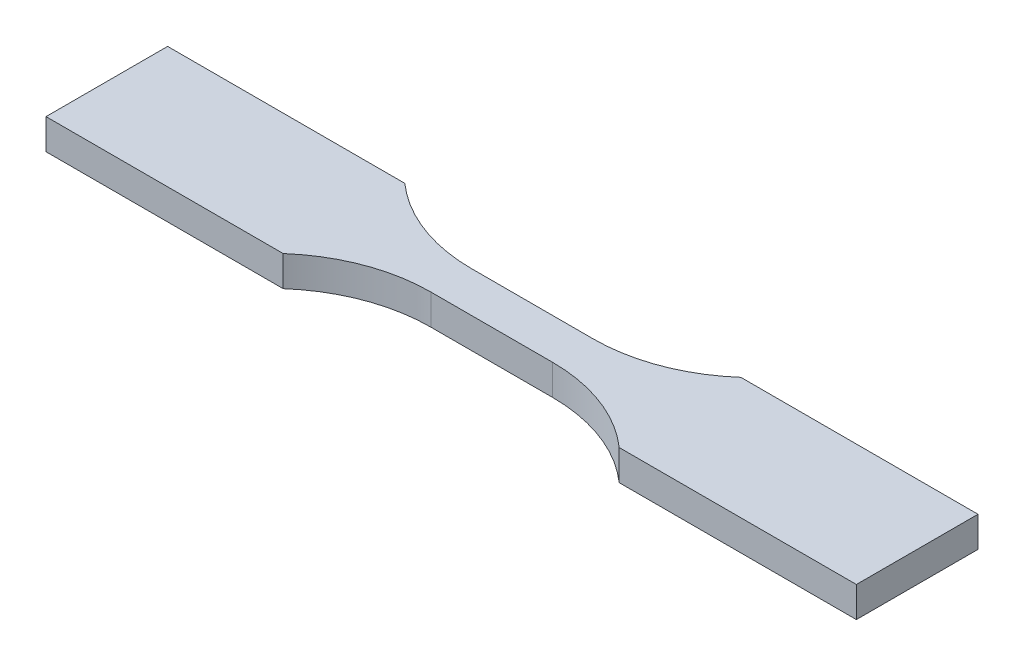
SolidWorks part; units mm, degrees
ref_plane "Front Plane" through (0, 0, 0) normal (0, 0, 1) x (1, 0, 0)
ref_plane "Top Plane" through (0, 0, 0) normal (0, 1, 0) x (1, 0, 0)
ref_plane "Right Plane" through (0, 0, 0) normal (1, 0, 0) x (0, 0, -1)
sketch "Sketch1" plane through (0, 0, 0) normal (0, 1, 0) x (1, 0, 0)
  line L0 (0, 1.59) -> (4.765, 1.59)
  line L2 (0, 0) -> (0, 1.59)
  line L3 (0, 0) -> (31.75, 0)
  line L4 (31.75, 0) -> (31.75, 4.765)
  line L5 (0, 0) -> (-2.4294, 0) construction
  line L7 (13.1653, 4.765) -> (31.75, 4.765)
  line L10 (0, 0) -> (0, -2.6558) construction
  arc A0 (4.765, 1.59) -> (13.1653, 4.765) centre (4.765, 14.29) ccw
  dimension "D3" = 12.7
  dimension "D1" = 3.18
  dimension "D2" = 63.5
  dimension "D4" = 9.53
  dimension "D5" = 9.53
extrude "Boss-Extrude1" add sketch "Sketch1" along normal blind 2.385
mirror "Mirror1" about plane through (0, 0, 0) normal (1, 0, 0) of "Boss-Extrude1"
scale "Scale1" scale about centroid uniform scaling yes scale factor 0.3144
